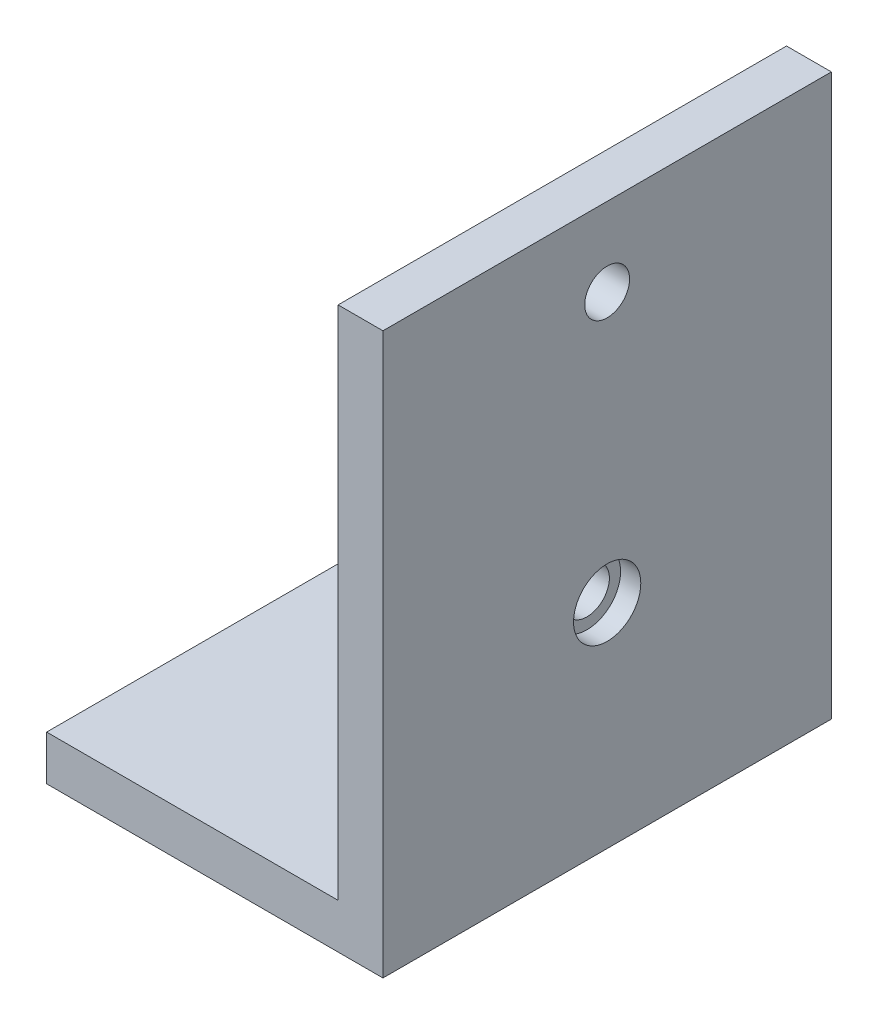
SolidWorks part; units mm, degrees
ref_plane "Alzado" through (0, 0, 0) normal (0, 0, 1) x (1, 0, 0)
ref_plane "Planta" through (0, 0, 0) normal (0, 1, 0) x (1, 0, 0)
ref_plane "Vista lateral" through (0, 0, 0) normal (1, 0, 0) x (0, 0, -1)
sketch "Croquis1" plane through (0, 0, 0) normal (0, 0, 1) x (1, 0, 0)
  line L0 (0, 125) -> (0, 0)
  line L1 (0, 0) -> (-75, 0)
  dimension "D1" = 125
  dimension "D2" = 75
extrude "Extruir-Lámina1" add sketch "Croquis1" along normal blind 100 thin
sketch "Croquis2" plane through (0, 0, 0) normal (1, 0, 0) x (0, 0, -1)
  line L0 (-50, 125) -> (-50, 107.5) construction
  line L1 (-100, 125) -> (0, 125) construction
  circle A0 centre (-50, 107.5) radius 5
  circle A1 centre (-50, 47.5) radius 5
  dimension "D1" = 10
  dimension "D3" = 10
  dimension "D4" = 60
  dimension "D2" = 17.5
extrude "Cortar-Extruir1" cut sketch "Croquis2" against normal blind 10
sketch "Croquis3" plane through (0, 0, 0) normal (1, 0, 0) x (0, 0, -1)
  circle A0 centre (-50, 47.5) radius 7.5
  dimension "D1" = 15
extrude "Cortar-Extruir2" cut sketch "Croquis3" against normal blind 4.5
